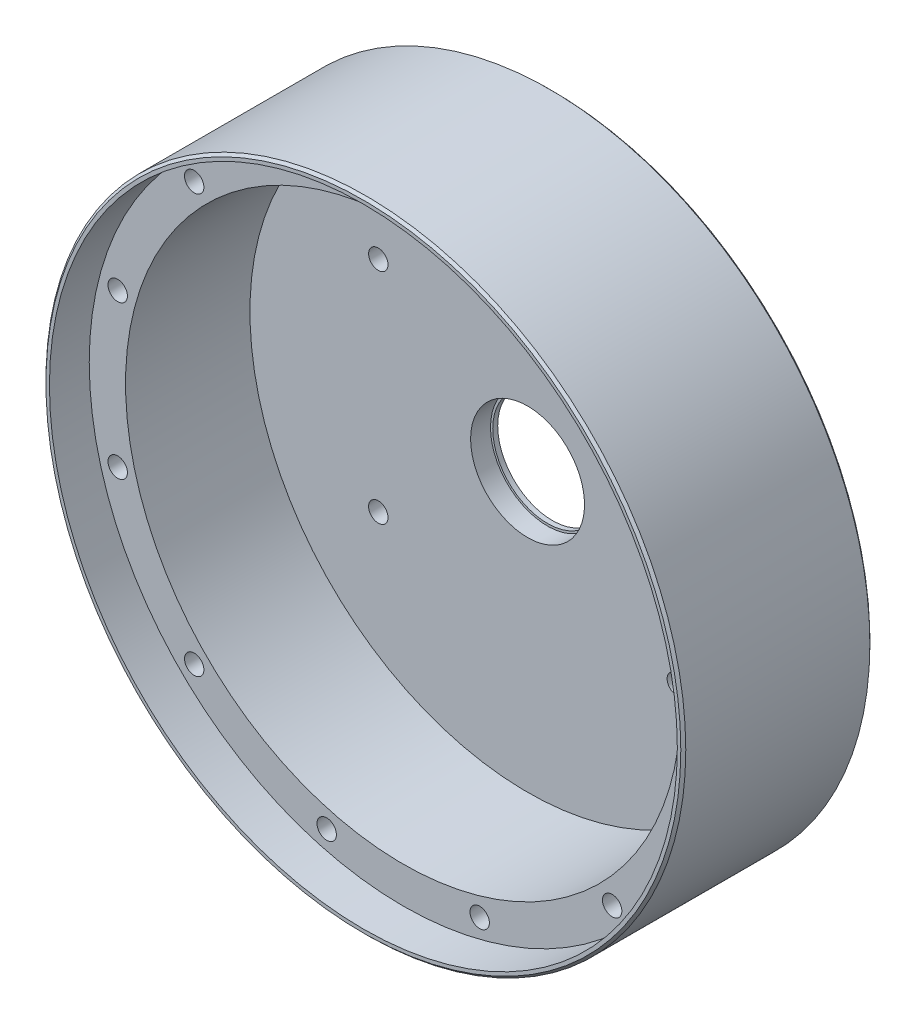
SolidWorks part; units mm, degrees
material "ABS"
ref_plane "Front Plane" through (0, 0, 0) normal (0, 0, 1) x (1, 0, 0)
ref_plane "Top Plane" through (0, 0, 0) normal (0, 1, 0) x (1, 0, 0)
ref_plane "Right Plane" through (0, 0, 0) normal (1, 0, 0) x (0, 0, -1)
sketch "Actuator Housing Mount" plane through (0, 0, 19) normal (0, 0, 1) x (1, 0, 0)
  line L0 (0, 0) -> (63, 0) construction
  line L1 (0, 0) -> (62.0607, 16.6291) construction
  circle A1 centre (57.376, 15.3739) radius 3.6 construction
  circle A2 centre (0, 0) radius 55.8
  circle A3 centre (57.376, 15.3739) radius 1.6
  circle A4 centre (57.376, -15.3739) radius 1.6
  circle A5 centre (42.0021, -42.0021) radius 1.6
  circle A6 centre (15.3739, -57.376) radius 1.6
  circle A7 centre (-15.3739, -57.376) radius 1.6
  circle A8 centre (-42.0021, -42.0021) radius 1.6
  circle A9 centre (-57.376, -15.3739) radius 1.6
  circle A10 centre (-57.376, 15.3739) radius 1.6
  circle A11 centre (-42.0021, 42.0021) radius 1.6
  circle A12 centre (-15.3739, 57.376) radius 1.6
  circle A13 centre (15.3739, 57.376) radius 1.6
  circle A14 centre (42.0021, 42.0021) radius 1.6
  circle A15 centre (0, 0) radius 64.3
  point P35 (0, 0)
extrude "Actuator Housing Wall" add sketch "Actuator Housing Mount" against normal blind 25
sketch "Sketch2" plane through (0, 0, -6) normal (0, 0, -1) x (-1, 0, 0)
  circle A0 centre (0, 0) radius 64.3
  circle A1 centre (0, 0) radius 64.3 construction
  circle M2 centre (-42.0021, 42.0021) radius 1.6
  circle M3 centre (-15.3739, 57.376) radius 1.6
  circle M4 centre (15.3739, 57.376) radius 1.6
  circle M5 centre (42.0021, 42.0021) radius 1.6
  circle M6 centre (57.376, 15.3739) radius 1.6
  circle M7 centre (57.376, -15.3739) radius 1.6
  circle M8 centre (42.0021, -42.0021) radius 1.6
  circle M9 centre (15.3739, -57.376) radius 1.6
  circle M10 centre (-15.3739, -57.376) radius 1.6
  circle M11 centre (-42.0021, -42.0021) radius 1.6
  circle M12 centre (0, 0) radius 55.8
  circle M13 centre (-57.376, -15.3739) radius 1.6
  circle M14 centre (-57.376, 15.3739) radius 1.6
  circle M15 centre (0, 0) radius 64.3
extrude "Boss-Extrude2" add sketch "Sketch2" along normal blind 5 contours M15 M3 M5 M7 M9 M11 M13 M14 M12 M10 M8 M6 M4 M2 | M12
sketch "Sketch3" plane through (0, 0, -11) normal (0, 0, -1) x (-1, 0, 0)
  circle A0 centre (0, 0) radius 11.45
  dimension "D1" = 22.9
extrude "Cut-Extrude1" cut sketch "Sketch3" along normal blind 4 from surface at -5 starting at face at (55.8, 0, -6)
sketch "Sketch4" plane through (0, 0, -11) normal (0, 0, -1) x (-1, 0, 0)
  circle A0 centre (0, 0) radius 11
  dimension "D1" = 22
extrude "Cut-Extrude2" cut sketch "Sketch4" against normal blind 4
sketch "Sketch6" plane through (0, 0, 19) normal (0, 0, 1) x (1, 0, 0)
  circle A0 centre (0, 0) radius 64.3
  circle A1 centre (0, 0) radius 63.1
  dimension "D1" = 128.6
  dimension "D2" = 126.2
extrude "Boss-Extrude3" add sketch "Sketch6" along normal blind 8
sketch "Sketch7" plane through (0, 0, 19) normal (0, 0, 1) x (1, 0, 0)
  circle A0 centre (57.376, -15.3739) radius 1.95
  circle A1 centre (42.0021, -42.0021) radius 1.95
  circle A2 centre (15.3739, -57.376) radius 1.95
  circle A3 centre (-15.3739, -57.376) radius 1.95
  circle A4 centre (-42.0021, -42.0021) radius 1.95
  circle A5 centre (-57.376, -15.3739) radius 1.95
  circle A6 centre (-57.376, 15.3739) radius 1.95
  circle A7 centre (-42.0021, 42.0021) radius 1.95
  circle A8 centre (-15.3739, 57.376) radius 1.95
  circle A9 centre (15.3739, 57.376) radius 1.95
  circle A10 centre (42.0021, 42.0021) radius 1.95
  circle A11 centre (57.376, 15.3739) radius 1.95
  point P27 (0, 0)
  dimension "D1" = 12
  dimension "M3 Insert" = 3.9
extrude "M3 Insert L12" cut sketch "Sketch7" against normal blind 12
chamfer "Chamfer2" distance 0.5 angle 45 2 edges at (64.3, 0, 27) (-64.3, 0, -11)
sketch "Sketch8" plane through (0, 0, 27) normal (0, 0, 1) x (1, 0, 0)
  line L1 (-5.1219, -61) -> (5.1219, -61)
  line L2 (-5.1219, -61) -> (-5.1219, -65.6855)
  line L3 (-5.1219, -65.6855) -> (5.1219, -65.6855)
  line L4 (5.1219, -61) -> (5.1219, -65.6855)
  dimension "D1" = 10.2438
sketch "Sketch9" plane through (0, 0, -11) normal (0, 0, -1) x (-1, 0, 0)
  line L1 (-30, -22) -> (30, -22) construction
  line L2 (-30, -22) -> (-30, 22) construction
  line L3 (-30, 22) -> (30, 22) construction
  line L4 (30, -22) -> (30, 22) construction
  line L5 (-30, -22) -> (30, 22) construction
  line L6 (-30, 22) -> (30, -22) construction
  circle A0 centre (-30, 22) radius 1.95
  circle A1 centre (30, 22) radius 1.95
  circle A2 centre (30, -22) radius 1.95
  circle A3 centre (-30, -22) radius 1.95
  point P0 (0, 0)
  dimension "D3" = 3.9
  dimension "D1" = 60
  dimension "D2" = 44
extrude "Cut-Extrude5" cut sketch "Sketch9" against normal blind 10
